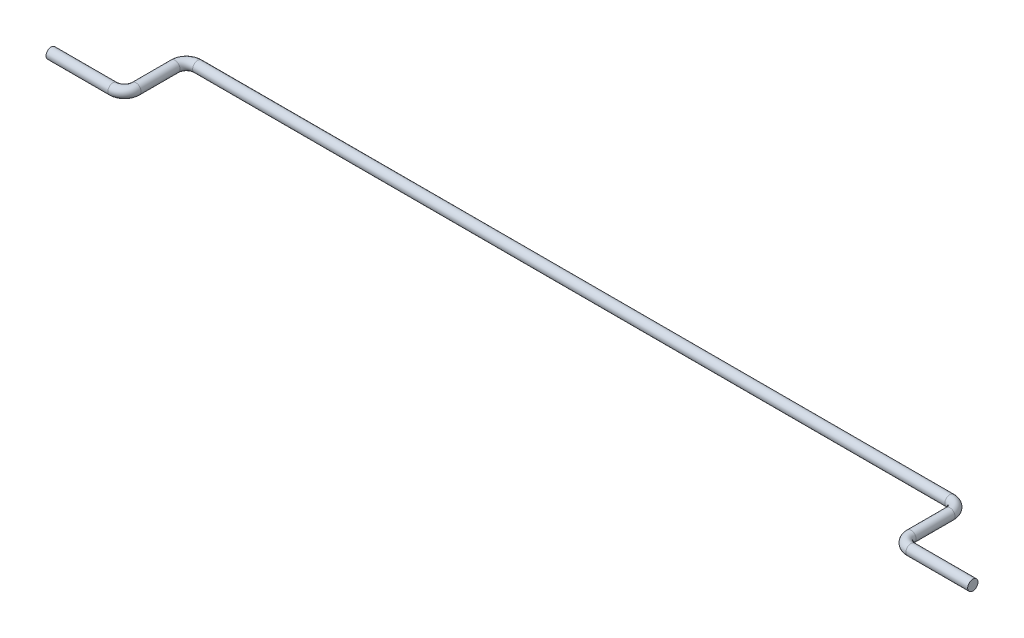
SolidWorks part; units mm, degrees
ref_plane "Front Plane" through (0, 0, 0) normal (0, 0, 1) x (1, 0, 0)
ref_plane "Top Plane" through (0, 0, 0) normal (0, 1, 0) x (1, 0, 0)
ref_plane "Right Plane" through (0, 0, 0) normal (1, 0, 0) x (0, 0, -1)
sketch "Sketch1" plane through (0, 0, 0) normal (0, 1, 0) x (1, 0, 0)
  line L0 (0, 0) -> (6.858, 0)
  line L1 (8.128, 1.27) -> (8.128, 5.588)
  line L2 (9.398, 6.858) -> (92.7862, 6.858)
  line L3 (94.0562, 5.588) -> (94.0562, 1.27)
  line L4 (95.3262, 0) -> (102.1842, 0)
  arc A0 (94.0562, 1.27) -> (95.3262, 0) centre (95.3262, 1.27) ccw
  arc A1 (6.858, 0) -> (8.128, 1.27) centre (6.858, 1.27) ccw
  arc A2 (8.128, 5.588) -> (9.398, 6.858) centre (9.398, 5.588) cw
  arc A3 (92.7862, 6.858) -> (94.0562, 5.588) centre (92.7862, 5.588) cw
  point P11 (8.128, 0)
  point P14 (8.128, 6.858)
  point P17 (94.0562, 6.858)
  dimension "D4" = 1.27
  dimension "D5" = 1.27
  dimension "D1" = 8.128
  dimension "D2" = 6.858
  dimension "D3" = 85.9282
sketch "Sketch2" plane through (0, 0, 0) normal (1, 0, 0) x (0, 0, -1)
  circle A0 centre (0, 0) radius 0.5715
  dimension "D1" = 1.143
sweep "Sweep1" add profiles "Sketch2" path "Sketch1"
